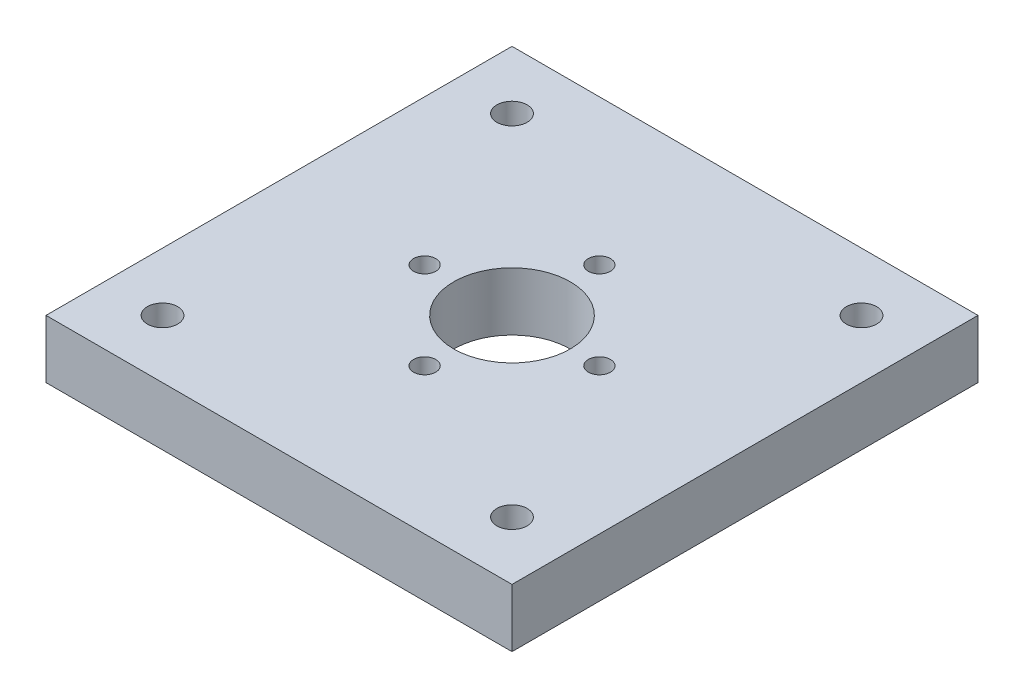
SolidWorks part; units mm, degrees
ref_plane "Front Plane" through (0, 0, 0) normal (0, 0, 1) x (1, 0, 0)
ref_plane "Top Plane" through (0, 0, 0) normal (0, 1, 0) x (1, 0, 0)
ref_plane "Right Plane" through (0, 0, 0) normal (1, 0, 0) x (0, 0, -1)
sketch "Sketch1" plane through (0, 0, 0) normal (0, 1, 0) x (1, 0, 0)
  line L0 (0, 2) -> (0, -2) construction
  line L1 (-2, 2) -> (2, 2)
  line L2 (-2, 2) -> (-2, -2)
  line L3 (-2, -2) -> (2, -2)
  line L4 (2, 2) -> (2, -2)
  line L5 (-2, 2) -> (2, -2) construction
  line L6 (-2, -2) -> (2, 2) construction
  line L7 (-2, 0) -> (2, 0) construction
  circle A0 centre (0, 0) radius 0.75 construction
  circle A1 centre (-1.5, 1.5) radius 0.13
  circle A2 centre (-1.5, -1.5) radius 0.13
  circle A4 centre (0, 0.75) radius 0.095
  circle A7 centre (0, 0) radius 0.5
  circle A8 centre (1.5, -1.5) radius 0.13
  circle A9 centre (1.5, 1.5) radius 0.13
  circle A10 centre (0.75, 0) radius 0.095
  circle A11 centre (0, -0.75) radius 0.095
  circle A12 centre (-0.75, 0) radius 0.095
  point P0 (0, 0)
  point P32 (0, 0)
  dimension "D3" = 0.5
  dimension "D4" = 0.5
  dimension "D5" = 0.5
  dimension "D6" = 0.5
  dimension "D7" = 0.26
  dimension "D8" = 0.26
  dimension "D9" = 1
  dimension "D10" = 1.5
  dimension "D11" = 0.19
  dimension "D13" = 3
  dimension "D15" = 3
  dimension "D16" = 0.19
  dimension "D1" = 4
  dimension "D2" = 4
  dimension "D14" = 2
  dimension "D12" = 4
extrude "Boss-Extrude1" add sketch "Sketch1" along normal blind 0.5
